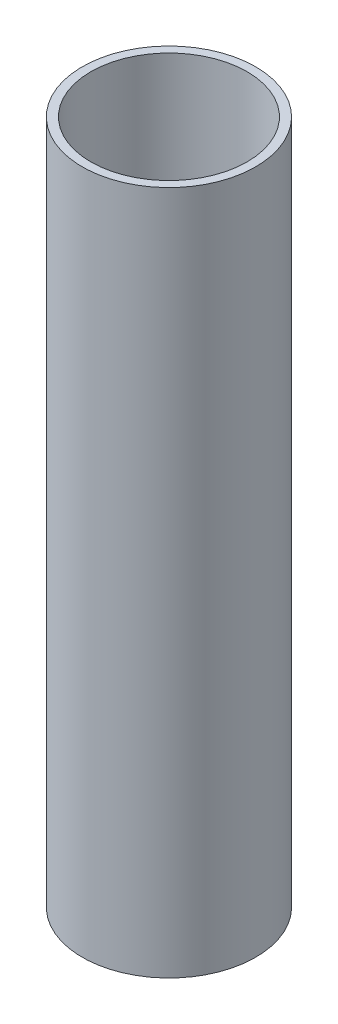
SolidWorks part; units mm, degrees
ref_plane "Front Plane" through (0, 0, 0) normal (0, 0, 1) x (1, 0, 0)
ref_plane "Top Plane" through (0, 0, 0) normal (0, 1, 0) x (1, 0, 0)
ref_plane "Right Plane" through (0, 0, 0) normal (1, 0, 0) x (0, 0, -1)
sketch "Sketch1" plane through (0, 0, 0) normal (0, 1, 0) x (1, 0, 0)
  circle A0 centre (0, 0) radius 19.304
  dimension "D1" = 38.608
extrude "Boss-Extrude1" add sketch "Sketch1" along normal mid plane 152.4
sketch "Sketch2" plane through (0, 76.2, 0) normal (0, 1, 0) x (1, 0, 0)
  circle A0 centre (0, 0) radius 17.399
  dimension "D1" = 34.798
extrude "Cut-Extrude1" cut sketch "Sketch2" against normal through all
equation "\"t\"=0.1"
